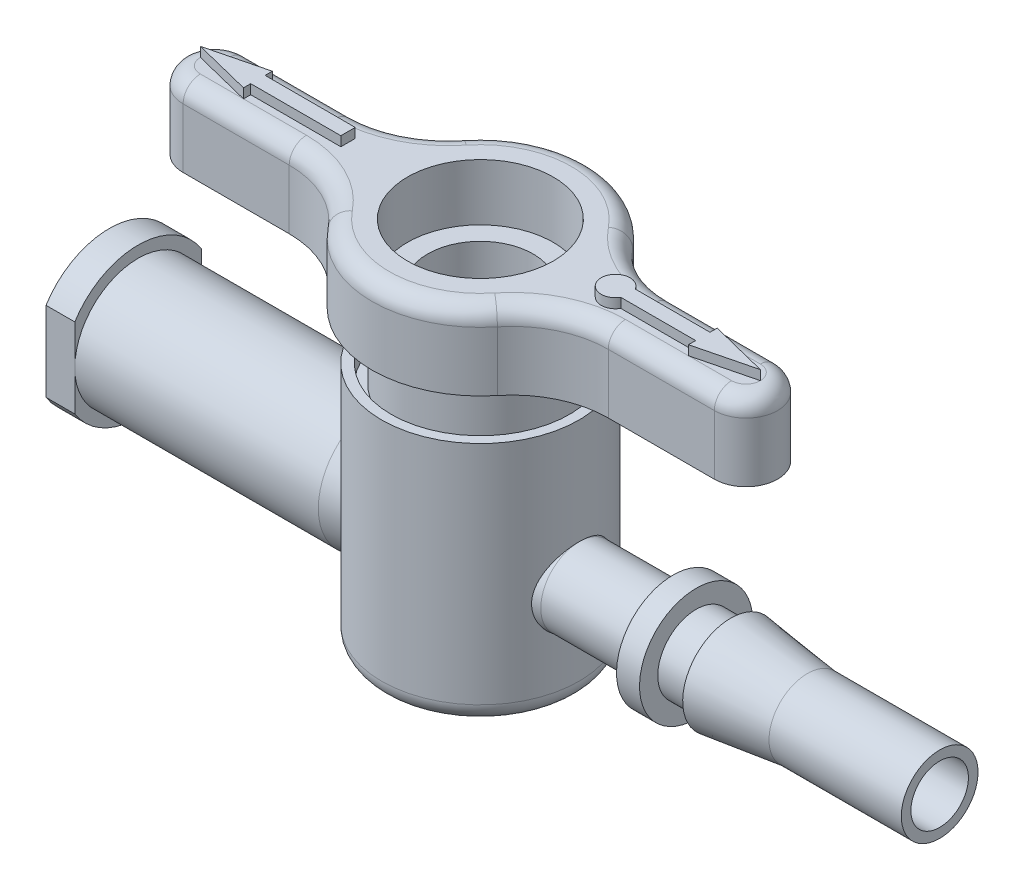
SolidWorks part; units mm, degrees
material "PC"
ref_plane "Front Plane" through (0, 0, 0) normal (0, 0, 1) x (1, 0, 0)
ref_plane "Top Plane" through (0, 0, 0) normal (0, 1, 0) x (1, 0, 0)
ref_plane "Right Plane" through (0, 0, 0) normal (1, 0, 0) x (0, 0, -1)
sketch "Sketch1" plane through (0, 0, 0) normal (0, 1, 0) x (1, 0, 0)
  circle A0 centre (0, 0) radius 5.15
  dimension "D1" = 10.3
extrude "Boss-Extrude1" add sketch "Sketch1" along normal blind 12.8
fillet "Fillet1" radius 1 1 edges at (0, 0, 5.15)
sketch "Sketch2" plane through (0, 0, 0) normal (0, 0, 1) x (1, 0, 0)
  line L0 (-19.35, 5.3) -> (23.95, 5.3) construction
  line L1 (-5.15, 12.8) -> (-5.15, 1) construction
  line L2 (-19.35, 3.175) -> (-19.35, 1.4)
  line L3 (-19.35, 1.4) -> (-17.85, 1.4)
  line L4 (-17.85, 1.4) -> (-17.85, 2)
  line L5 (-17.85, 2) -> (-5.15, 2)
  line L6 (-5.15, 2) -> (5.15, 3.3)
  line L7 (5.15, 1) -> (5.15, 12.8) construction
  line L8 (5.15, 3.3) -> (10.05, 3.3)
  line L9 (10.05, 3.3) -> (10.05, 2.35)
  line L10 (10.05, 2.35) -> (11.25, 2.35)
  line L11 (11.25, 2.35) -> (11.25, 3.3)
  line L12 (11.25, 3.3) -> (13.05, 3.3)
  line L13 (13.05, 3.3) -> (13.05, 2.8)
  line L14 (13.05, 2.8) -> (17.05, 3.3)
  line L15 (17.05, 3.3) -> (23.95, 3.3)
  line L16 (23.95, 3.3) -> (23.95, 3.8)
  line L17 (23.95, 3.8) -> (-5.15, 3.8)
  line L18 (-5.15, 3.8) -> (-10.35, 3.175)
  line L19 (-10.35, 3.175) -> (-19.35, 3.175)
  dimension "D1" = 14.2
  dimension "D2" = 43.3
  dimension "D3" = 6.6
  dimension "D4" = 2
  dimension "D5" = 4.25
  dimension "D6" = 3
  dimension "D7" = 4
  dimension "D8" = 7.8
  dimension "D9" = 1.5
  dimension "D10" = 9
  dimension "D11" = 12.7
  dimension "D12" = 1.2
  dimension "D13" = 5.9
  dimension "D14" = 5
  dimension "D15" = 1.8
  dimension "D16" = 4
revolve "Revolve1" add sketch "Sketch2" angle 360 about L0
sketch "Sketch3" plane through (0, 12.8, 0) normal (0, 1, 0) x (1, 0, 0)
  circle A2 centre (0, 0) radius 4.15
  circle A3 centre (0, 0) radius 4.15
  dimension "D1" = 1
extrude "Cut-Extrude1" cut sketch "Sketch3" against normal offset from surface (11.8 mm away) 1 up to face at (0, 0, 4.15)
sketch "Sketch4" plane through (23.95, 0, 0) normal (1, 0, 0) x (0, 0, -1)
  circle A0 centre (0, 5.3) radius 1.5 construction
  circle A1 centre (0, 5.3) radius 1.5
extrude "Cut-Extrude2" cut sketch "Sketch4" against normal through all
sketch "Sketch5" plane through (0, 12.8, 0) normal (0, 1, 0) x (1, 0, 0)
  circle A0 centre (0, 0) radius 4.15 construction
  circle A1 centre (0, 0) radius 4.15
  circle A2 centre (0, 0) radius 4.65
  dimension "D1" = 0.5
extrude "Cut-Extrude3" cut sketch "Sketch5" against normal blind 3
sketch "Sketch6" plane through (0, 12.8, 0) normal (0, 1, 0) x (1, 0, 0)
  circle A0 centre (0, 0) radius 4.65 construction
  circle A1 centre (0, 0) radius 4.65
  circle A2 centre (0, 0) radius 5.05
  dimension "D1" = 0.4
extrude "Cut-Extrude4" cut sketch "Sketch6" against normal blind 0.5 from offset 1 offset against normal yes
sketch "Sketch11" plane through (0, 0, 0) normal (0, 1, 0) x (1, 0, 0)
  line L0 (-5.15, 3.3) -> (-17.85, 3.3) construction
  line L1 (-17.85, -3.3) -> (-5.15, -3.3) construction
  line L2 (-17.85, -3.9) -> (-17.85, 3.9) construction
  line L3 (-19.35, -3.9) -> (-17.85, -3.9) construction
  line L4 (-19.35, 3.9) -> (-19.35, -3.9) construction
  line L5 (-17.85, 3.9) -> (-19.35, 3.9) construction
  line L6 (-17.85, 3.3) -> (-19.35, 3.3)
  line L7 (-19.35, -3.3) -> (-17.85, -3.3)
  line L8 (-17.85, -3.9) -> (-17.85, -3.3)
  line L9 (-19.35, -3.9) -> (-17.85, -3.9)
  line L10 (-19.35, 3.9) -> (-19.35, 3.3)
  line L11 (-17.85, 3.9) -> (-19.35, 3.9)
  line L12 (-19.35, -3.3) -> (-19.35, -3.9)
  line L13 (-17.85, 3.3) -> (-17.85, 3.9)
extrude "Cut-Extrude7" cut sketch "Sketch11" against normal through all and the other way through all
sketch "Sketch7" plane through (0, 0, 0) normal (0, 0, 1) x (1, 0, 0)
  line L0 (0, 16.35) -> (0, 1.2) construction
  line L1 (2.15, 1.2) -> (4.15, 1.2)
  line L4 (5.05, 11.3) -> (5.05, 11.8) construction
  line L5 (5.05, 11.3) -> (-5.05, 11.3) construction
  line L6 (4.65, 9.8) -> (4.65, 11.3) construction
  line L7 (4.65, 9.8) -> (-4.65, 9.8) construction
  line L8 (4.15, 6.8) -> (4.15, 9.8) construction
  line L10 (2.15, 1.2) -> (2.15, 2.2)
  line L11 (5.05, 11.3) -> (5.05, 11.8)
  line L12 (5.05, 11.3) -> (4.65, 11.3)
  line L13 (4.65, 9.8) -> (4.65, 11.3)
  line L14 (4.65, 9.8) -> (4.15, 9.8)
  line L15 (4.15, 1.2) -> (4.15, 9.8)
  line L16 (-5.05, 11.8) -> (5.05, 11.8) construction
  line L17 (2.15, 2.2) -> (0, 2.2)
  line L18 (4.15, 11.8) -> (5.05, 11.8)
  line L19 (4.15, 11.8) -> (4.15, 16.35)
  line L20 (4.15, 16.35) -> (2.75, 16.35)
  line L21 (2.75, 16.35) -> (2.75, 7.35)
  line L22 (2.75, 7.35) -> (0, 7.35)
  line L23 (0, 7.35) -> (0, 2.2)
  line L24 (5.15, 1) -> (-5.15, 1) construction
  line L25 (4.65, 12.8) -> (-4.65, 12.8) construction
  dimension "D1" = 0.2
  dimension "D2" = 2
  dimension "D3" = 1
  dimension "D4" = 5.5
  dimension "D5" = 9
  dimension "D6" = 3.55
revolve "Revolve2" add sketch "Sketch7" angle 360 about L0
sketch "Sketch8" plane through (0, 12.8, 0) normal (0, 1, 0) x (1, 0, 0)
  line L0 (-8.3187, 1.65) -> (-13.85, 1.65)
  line L1 (-13.85, -1.65) -> (-8.3187, -1.65)
  line L2 (0, 5.65) -> (0, -5.65) construction
  line L3 (13.85, -1.65) -> (8.3187, -1.65)
  line L4 (8.3187, 1.65) -> (13.85, 1.65)
  circle A0 centre (0, 0) radius 3.8
  arc A1 (-4.4132, -3.5279) -> (4.4132, -3.5279) centre (0, 0) ccw
  arc A2 (-13.85, 1.65) -> (-13.85, -1.65) centre (-13.85, 0) ccw
  arc A3 (4.4132, 3.5279) -> (-4.4132, 3.5279) centre (0, 0) ccw
  arc A4 (-8.3187, -1.65) -> (-4.4132, -3.5279) centre (-8.3187, -6.65) cw
  arc A5 (-8.3187, 1.65) -> (-4.4132, 3.5279) centre (-8.3187, 6.65) ccw
  arc A6 (8.3187, 1.65) -> (4.4132, 3.5279) centre (8.3187, 6.65) cw
  arc A7 (8.3187, -1.65) -> (4.4132, -3.5279) centre (8.3187, -6.65) ccw
  arc A8 (13.85, 1.65) -> (13.85, -1.65) centre (13.85, 0) cw
  point P13 (-5.4037, -1.65)
  point P16 (-5.4037, 1.65)
  dimension "D1" = 7.6
  dimension "D2" = 11.3
  dimension "D4" = 15.5
  dimension "D5" = 5
  dimension "D3" = 3.3
extrude "Boss-Extrude2" add sketch "Sketch8" along normal blind 4 from offset 2.5
fillet "Fillet2" radius 0.9 12 edges at (-6.1519, 19.3, 2.1439) (-11.0843, 19.3, 1.65) (-15.5, 19.3, 0) (-11.0843, 19.3, -1.65) (-6.1519, 19.3, -2.1439) (0, 19.3, -5.65) (6.1519, 19.3, -2.1439) (11.0843, 19.3, -1.65) (15.5, 19.3, 0) (11.0843, 19.3, 1.65) (6.1519, 19.3, 2.1439) (0, 19.3, 5.65)
sketch "Sketch9" plane through (23.95, 0, 0) normal (1, 0, 0) x (0, 0, -1)
  circle A0 centre (0, 5.3) radius 1
  dimension "D1" = 2
extrude "Cut-Extrude5" cut sketch "Sketch9" against normal through all
sketch "Sketch10" plane through (0, 19.3, 0) normal (0, 1, 0) x (1, 0, 0)
  line L0 (-6.9, 0.375) -> (-11.6, 0.375)
  line L1 (-11.6, 0.375) -> (-11.6, 0.75)
  line L2 (-11.6, 0.75) -> (-14.6, 0)
  line L3 (-14.6, 0) -> (-11.6, -0.75)
  line L4 (-11.6, -0.75) -> (-11.6, -0.375)
  line L5 (-11.6, -0.375) -> (-6.9, -0.375)
  line L6 (-6.9, -0.375) -> (-6.9, 0.375)
  line L7 (0, 2.75) -> (0, -2.75) construction
  line L9 (11.6, -0.375) -> (7.6995, -0.375)
  line L10 (11.6, -0.75) -> (11.6, -0.375)
  line L11 (14.6, 0) -> (11.6, -0.75)
  line L12 (11.6, 0.75) -> (14.6, 0)
  line L13 (11.6, 0.375) -> (11.6, 0.75)
  line L14 (7.6995, 0.375) -> (11.6, 0.375)
  arc A0 (-13.85, 0.75) -> (-13.85, -0.75) centre (-13.85, 0) ccw construction
  circle A1 centre (0, 0) radius 2.75 construction
  arc A2 (7.6995, 0.375) -> (7.6995, -0.375) centre (7.05, 0) ccw
  point P8 (-6.9, 0)
  dimension "D5" = 1.5
  dimension "D6" = 8.3
  dimension "D1" = 7.7
  dimension "D2" = 0.75
  dimension "D3" = 1.5
  dimension "D4" = 3
extrude "Boss-Extrude3" add sketch "Sketch10" along normal blind 0.5
move or copy body "Body-Move/Copy1" [suppressed] bodies to move or copy 114 copy no rotation origin (0, 0, 0) rotation axis (0, 1, 0) rotation angle 90
